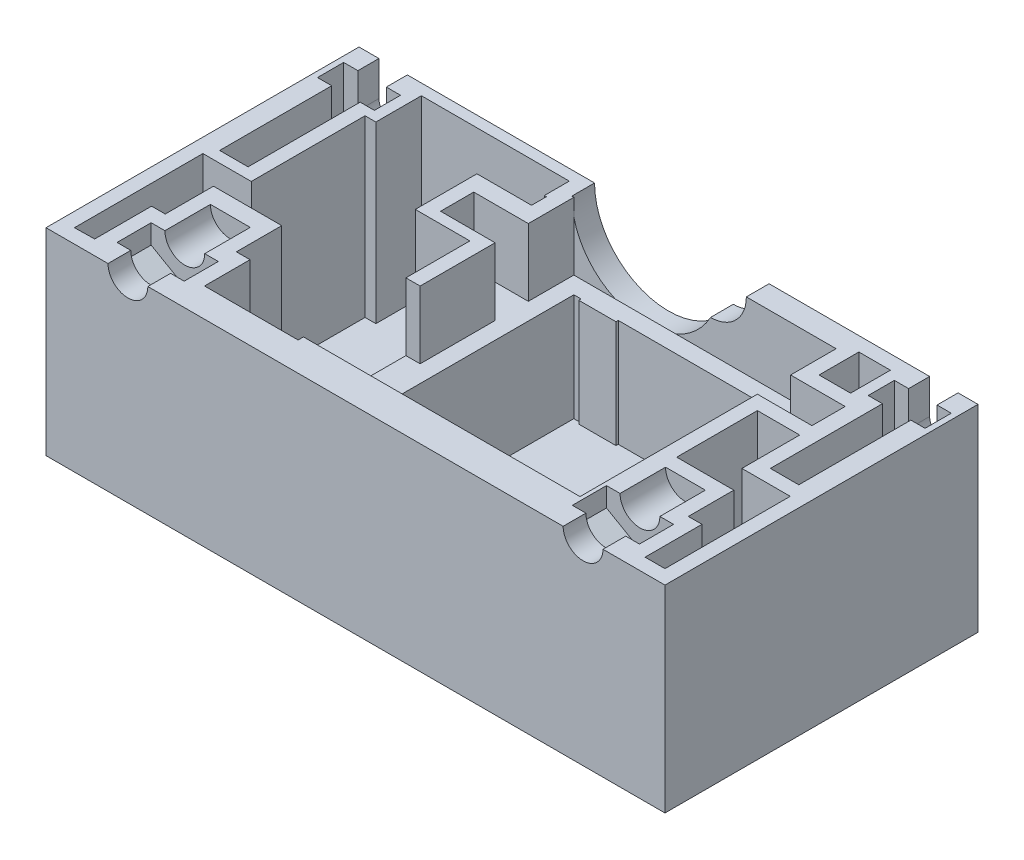
SolidWorks part; units mm, degrees
material "PLA"
ref_plane "Front Plane" through (0, 0, 0) normal (0, 0, 1) x (1, 0, 0)
ref_plane "Top Plane" through (0, 0, 0) normal (0, 1, 0) x (1, 0, 0)
ref_plane "Right Plane" through (0, 0, 0) normal (1, 0, 0) x (0, 0, -1)
sketch "Sketch1" plane through (0, 0, 0) normal (0, 1, 0) x (1, 0, 0)
  line L1 (27.2, -13.755) -> (-27.2, -13.755)
  line L2 (27.2, -13.755) -> (27.2, 13.755)
  line L3 (27.2, 13.755) -> (-27.2, 13.755)
  line L4 (-27.2, -13.755) -> (-27.2, 13.755)
  line L5 (27.2, -13.755) -> (-27.2, 13.755) construction
  line L6 (27.2, 13.755) -> (-27.2, -13.755) construction
  point P0 (0, 0)
  dimension "D1" = 54.4
  dimension "D2" = 27.51
extrude "Boss-Extrude1" add sketch "Sketch1" along normal blind 17.35
sketch "Sketch2" plane through (0, 17.35, 0) normal (0, 1, 0) x (1, 0, 0)
  line L0 (-27.2, -13.755) -> (-25.95, -13.755) construction
  line L1 (-27.2, -13.755) -> (27.2, -13.755) construction
  line L2 (-25.95, -13.755) -> (-25.95, -12.505) construction
  line L19 (-7.75, 12.7853) -> (-20.75, 12.7853)
  line L20 (-25.95, -12.505) -> (-25.95, -1.2147)
  line L21 (-25.95, -1.2147) -> (-21.7, -1.2147)
  line L22 (-21.7, -1.2147) -> (-21.7, 8.7853)
  line L23 (-21.7, 8.7853) -> (-20.75, 8.7853)
  line L26 (-20.75, 12.7853) -> (-20.75, 8.7853)
  line L27 (-7.75, 12.7853) -> (-7.75, 10.5853)
  line L28 (-7.75, 10.5853) -> (-7.57, 10.5853)
  line L29 (-7.57, 10.5853) -> (-7.57, 9.2853)
  line L30 (-7.57, 9.2853) -> (-12.365, 9.2853)
  line L31 (-12.365, 9.2853) -> (-12.365, 3.8653)
  line L32 (-12.365, 3.8653) -> (-7.5693, 3.8653)
  line L33 (-7.5693, 3.8653) -> (-7.5693, -11.2247)
  line L34 (-7.5693, -11.2247) -> (-15.7993, -11.2247)
  line L35 (-15.7993, -11.2247) -> (-15.7993, -7.2247)
  line L36 (-15.7993, -7.2247) -> (-16.9993, -7.2247)
  line L37 (-16.9993, -7.2247) -> (-16.9993, -3.2369)
  line L38 (-16.9993, -3.2369) -> (-22.9993, -3.2369)
  line L39 (-22.9993, -3.2369) -> (-22.9993, -7.4761)
  line L40 (-22.9993, -7.4761) -> (-24.1993, -7.4761)
  line L41 (-24.1993, -7.4761) -> (-24.1993, -12.4761)
  line L42 (-25.95, -12.505) -> (-24.1993, -12.4761)
  dimension "D1" = 1.25
  dimension "D2" = 1.25
  dimension "D3" = 2.2
  dimension "D4" = 0.18
  dimension "D5" = 1.3
  dimension "D6" = 4.795
  dimension "D7" = 5.42
  dimension "D8" = 15.09
  dimension "D9" = 8.23
  dimension "D10" = 4
  dimension "D11" = 1.2
  dimension "D12" = 3.9878
  dimension "D13" = 6
  dimension "D14" = 1.2
  dimension "D15" = 5
  dimension "D17" = 13
  dimension "D19" = 0.95
  dimension "D21" = 4
  dimension "D22" = 10
  dimension "D23" = 11.2903
extrude "Cut-Extrude1" cut sketch "Sketch2" against normal blind 15.35
sketch "Sketch3" plane through (0, 17.35, 0) normal (0, 1, 0) x (1, 0, 0)
  line L0 (-27.2, -13.755) -> (-7.57, -13.755) construction
  line L1 (-27.2, -13.755) -> (27.2, -13.755) construction
  line L2 (-7.57, -13.755) -> (-7.57, -10.755) construction
  line L3 (-7.57, -10.755) -> (-7.57, -1.755)
  line L4 (-7.57, -1.755) -> (-6.32, -1.755)
  line L5 (-6.32, -1.755) -> (-6.32, 11.755)
  line L6 (-6.32, 11.755) -> (16.73, 11.755)
  line L7 (16.73, 11.755) -> (16.73, -10.755)
  line L8 (16.73, -10.755) -> (-7.57, -10.755)
  dimension "D1" = 19.63
  dimension "D2" = 3
  dimension "D3" = 9
  dimension "D4" = 1.25
  dimension "D5" = 13.51
  dimension "D6" = 23.05
extrude "Cut-Extrude2" cut sketch "Sketch3" against normal blind 5.92
sketch "Sketch4" plane through (0, 11.43, 0) normal (0, 1, 0) x (1, 0, 0)
  line L0 (16.73, 11.755) -> (15.23, 10.255) construction
  line L1 (15.23, 10.255) -> (15.23, -9.255)
  line L2 (15.23, -9.255) -> (-4.82, -9.255)
  line L3 (-4.82, -9.255) -> (-4.82, 10.255)
  line L4 (-4.82, 10.255) -> (-4.1839, 10.255)
  line L6 (-4.1839, 10.055) -> (-0.9167, 10.055)
  line L7 (-0.9167, 10.055) -> (-0.9167, 10.255)
  line L8 (15.23, 10.255) -> (-0.9167, 10.255)
  line L9 (-4.1839, 10.255) -> (-4.1839, 10.055)
  dimension "D1" = 1.5
  dimension "D2" = 1.5
  dimension "D3" = 19.51
  dimension "D4" = 19.51
  dimension "D5" = 20.05
  dimension "D6" = 0.2
  dimension "D7" = 0.636
  dimension "D8" = 0.2
extrude "Cut-Extrude3" cut sketch "Sketch4" against normal blind 9.43
sketch "Sketch5" plane through (0, 17.35, 0) normal (0, 1, 0) x (1, 0, 0)
  line L0 (-27.2, 13.755) -> (-11.115, 13.755) construction
  line L1 (27.2, 13.755) -> (-27.2, 13.755) construction
  line L2 (-11.115, 13.755) -> (-11.115, 7.755) construction
  line L3 (-11.115, 7.755) -> (-11.115, 4.835)
  line L4 (-11.115, 4.835) -> (-6.32, 4.835)
  line L5 (-6.32, 11.755) -> (-6.32, -1.755) construction
  line L6 (-6.32, 4.835) -> (-6.32, 7.755)
  line L7 (-6.32, 11.755) -> (-6.32, -1.755) construction
  line L8 (-6.32, 7.755) -> (-11.115, 7.755)
  line L9 (5.205, -9.255) -> (5.205, 21.1558) construction
  line L11 (-4.82, -9.255) -> (15.23, -9.255) construction
  line L12 (21.525, 13.755) -> (21.525, 7.755) construction
  line L13 (16.73, 7.755) -> (21.525, 7.755)
  line L14 (16.73, 4.835) -> (16.73, 7.755)
  line L15 (21.525, 4.835) -> (16.73, 4.835)
  line L16 (21.525, 7.755) -> (21.525, 4.835)
  dimension "D1" = 16.085
  dimension "D2" = 6
  dimension "D3" = 2.92
extrude "Cut-Extrude4" cut sketch "Sketch5" against normal up to surface (5.92 mm away) up to face at (1.3274, 11.43, -5.3275)
sketch "Sketch6" plane through (0, 17.35, 0) normal (0, 1, 0) x (1, 0, 0)
  line L0 (27.2, 13.755) -> (20.75, 13.755) construction
  line L1 (27.2, 13.755) -> (-27.2, 13.755) construction
  line L2 (20.75, 13.755) -> (20.75, 12.505) construction
  line L4 (20.75, 12.505) -> (17.98, 12.505)
  line L5 (20.75, 12.505) -> (20.75, 9.005)
  line L6 (20.75, 9.005) -> (17.98, 9.005)
  line L7 (17.98, 12.505) -> (17.98, 9.005)
  dimension "D1" = 6.45
  dimension "D2" = 1.25
  dimension "D3" = 2.77
  dimension "D4" = 3.5
extrude "Cut-Extrude5" cut sketch "Sketch6" against normal blind 15.35
sketch "Sketch7" plane through (0, 17.35, 0) normal (0, 1, 0) x (1, 0, 0)
  line L0 (27.2, 13.755) -> (27.2, 3.585) construction
  line L1 (27.2, -13.755) -> (27.2, 13.755) construction
  line L2 (27.2, 3.585) -> (21.7, 3.585) construction
  line L3 (21.7, 3.585) -> (17.98, 3.585)
  line L4 (17.98, 3.585) -> (17.98, -3.505)
  line L5 (17.98, -3.505) -> (23, -3.505)
  line L6 (23, -3.505) -> (23, -7.505)
  line L7 (23, -7.505) -> (24.2, -7.505)
  line L8 (24.2, -7.505) -> (24.2, -12.505)
  line L9 (24.2, -12.505) -> (25.95, -12.505)
  line L10 (25.95, -12.505) -> (25.95, -1.495)
  line L11 (25.95, -1.495) -> (21.7, -1.495)
  line L12 (21.7, 3.585) -> (21.7, -1.495)
  dimension "D1" = 5.5
  dimension "D2" = 10.17
  dimension "D3" = 3.72
  dimension "D4" = 7.09
  dimension "D5" = 5.02
  dimension "D6" = 4
  dimension "D7" = 1.2
  dimension "D8" = 5
  dimension "D9" = 1.75
  dimension "D10" = 11.01
  dimension "D11" = 4.25
extrude "Cut-Extrude6" cut sketch "Sketch7" against normal up to surface (15.35 mm away) up to face at (19.365, 2, -10.755)
sketch "Sketch8" plane through (0, 0, 13.755) normal (0, 0, 1) x (1, 0, 0)
  line L0 (-27.2, 17.35) -> (-21.75, 17.35) construction
  line L1 (-27.2, 17.35) -> (27.2, 17.35) construction
  line L2 (-21.75, 17.35) -> (-18.25, 17.35) construction
  line L3 (0, -9.5425) -> (0, 9.5425) construction
  circle A0 centre (-20, 17.35) radius 1.75
  circle A1 centre (20, 17.35) radius 1.75
  dimension "D1" = 5.45
  dimension "D2" = 3.5
extrude "Cut-Extrude7" cut sketch "Sketch8" against normal blind 9
sketch "Sketch9" plane through (0, 0, -13.755) normal (0, 0, -1) x (-1, 0, 0)
  line L0 (-27.2, 17.35) -> (-25.45, 17.35) construction
  line L1 (-27.2, 17.35) -> (27.2, 17.35) construction
  line L2 (-25.45, 17.35) -> (-25.45, 14.3)
  line L3 (0, 9.5425) -> (0, -9.5425) construction
  line L4 (-22.95, 14.3) -> (-22.95, 17.35)
  line L5 (-22.95, 17.35) -> (-25.45, 17.35)
  line L6 (27.2, 17.35) -> (25.45, 17.35) construction
  line L7 (22.95, 17.35) -> (25.45, 17.35)
  line L8 (22.95, 14.3) -> (22.95, 17.35)
  line L9 (25.45, 17.35) -> (25.45, 14.3)
  arc A0 (-25.45, 14.3) -> (-22.95, 14.3) centre (-24.2, 14.3) ccw
  arc A1 (25.45, 14.3) -> (22.95, 14.3) centre (24.2, 14.3) cw
  dimension "D1" = 1.75
  dimension "D2" = 3.05
  dimension "D3" = 2.5
extrude "Cut-Extrude8" cut sketch "Sketch9" against normal blind 14
sketch "Sketch10" plane through (0, 17.35, 0) normal (0, 1, 0) x (1, 0, 0)
  line L0 (-27.2, 13.755) -> (-26.7, 13.755) construction
  line L1 (-25.45, 13.755) -> (-27.2, 13.755) construction
  line L2 (-26.7, 13.755) -> (-26.7, 11.905) construction
  line L3 (-26.7, 11.905) -> (-21.7, 11.905)
  line L4 (-21.7, 11.905) -> (-21.7, 9.605)
  line L5 (-26.7, 11.905) -> (-26.7, 9.605)
  line L6 (-26.7, 9.605) -> (-21.7, 9.605)
  line L7 (0, -9.5425) -> (0, 9.5425) construction
  line L8 (26.7, 11.905) -> (26.7, 9.605)
  line L9 (26.7, 11.905) -> (21.7, 11.905)
  line L10 (21.7, 11.905) -> (21.7, 9.605)
  line L11 (26.7, 9.605) -> (21.7, 9.605)
  dimension "D1" = 0.5
  dimension "D2" = 1.85
  dimension "D3" = 5
  dimension "D4" = 2.3
extrude "Cut-Extrude9" cut sketch "Sketch10" against normal blind 4.3202
ref_plane "Plane1" through (0, 0, -11.755) normal (0, 0, -1) x (-1, 0, 0)
sketch "Sketch11" plane through (0, 0, -11.755) normal (0, 0, -1) x (-1, 0, 0)
  line L0 (-27.2, 17.35) -> (-27.2, 13.0298) construction
  line L1 (-27.2, 17.35) -> (-27.2, 0) construction
  line L2 (-27.2, 13.0298) -> (-26.4, 13.0298) construction
  line L3 (-26.4, 13.0298) -> (-26.4, 11.7597) construction
  line L4 (-26.4, 11.7597) -> (-24.2, 11.7597) construction
  line L5 (-24.2, 11.7597) -> (-24.2, 19.0949) construction
  line L6 (-26.4, 13.0298) -> (-24.2, 11.7597)
  line L7 (-26.4, 13.0298) -> (-22, 13.0298)
  line L8 (-22, 13.0298) -> (-24.2, 11.7597)
  line L9 (0, 9.5425) -> (0, -9.5425) construction
  line L10 (24.2, 11.7597) -> (24.2, 19.0949) construction
  line L11 (26.4, 11.7597) -> (24.2, 11.7597) construction
  line L12 (26.4, 13.0298) -> (26.4, 11.7597) construction
  line L13 (27.2, 13.0298) -> (26.4, 13.0298) construction
  line L14 (27.2, 17.35) -> (27.2, 13.0298) construction
  line L15 (22, 13.0298) -> (24.2, 11.7597)
  line L16 (26.4, 13.0298) -> (22, 13.0298)
  line L17 (26.4, 13.0298) -> (24.2, 11.7597)
  point P11 (-24.2, 13.0298)
  point P20 (24.2, 13.0298)
  dimension "D1" = 0.8
  dimension "D2" = 4.3202
  dimension "D3" = 2.2
  dimension "D4" = 1.2702
extrude "Cut-Extrude10" cut sketch "Sketch11" against normal blind 2
ref_plane "Plane2" through (0, 0, 11.755) normal (0, 0, 1) x (1, 0, 0)
sketch "Sketch13" plane through (0, 0, 11.755) normal (0, 0, 1) x (1, 0, 0)
  line L0 (-27.2, 17.35) -> (-22.9582, 17.35) construction
  line L1 (-27.2, 17.35) -> (-21.75, 17.35) construction
  line L2 (-22.9582, 17.35) -> (-17.0582, 17.35)
  line L3 (-18.25, 17.35) -> (18.25, 17.35) construction
  line L4 (-22.9582, 17.35) -> (-22.9582, 15.6468)
  line L5 (-22.9582, 15.6468) -> (-20.0082, 13.9437)
  line L6 (-17.0582, 17.35) -> (-17.0582, 15.6468)
  line L7 (-17.0582, 15.6468) -> (-20.0082, 13.9437)
  line L8 (0, -9.5425) -> (0, 9.5425) construction
  line L9 (27.2, 17.35) -> (22.9582, 17.35) construction
  line L10 (17.0582, 15.6468) -> (20.0082, 13.9437)
  line L11 (17.0582, 17.35) -> (17.0582, 15.6468)
  line L12 (22.9582, 15.6468) -> (20.0082, 13.9437)
  line L13 (22.9582, 17.35) -> (22.9582, 15.6468)
  line L14 (22.9582, 17.35) -> (17.0582, 17.35)
  dimension "D1" = 5.9
  dimension "D2" = 2.95
  dimension "D3" = 1.7032
  dimension "D4" = 1.7032
extrude "Cut-Extrude11" cut sketch "Sketch13" against normal blind 3
sketch "Sketch14" plane through (0, 0, -13.755) normal (0, 0, -1) x (-1, 0, 0)
  line L0 (-27.2, 17.35) -> (-8.84, 17.35) construction
  line L1 (-22.95, 17.35) -> (22.95, 17.35) construction
  line L2 (-8.84, 17.35) -> (6.5, 17.35)
  line L3 (-8.84, 17.35) -> (-8.84, 14.4012) construction
  line L4 (-8.84, 14.4012) -> (-6.7692, 14.4012) construction
  line L5 (-6.7692, 14.4012) -> (-6.7692, 14.215) construction
  line L6 (-6.7692, 14.215) -> (-5.694, 14.215) construction
  line L7 (-8.84, 17.35) -> (-5.7051, 17.35) construction
  line L8 (-5.694, 14.215) -> (-5.694, 10.8519) construction
  line L9 (-5.694, 10.8519) -> (-0.159, 10.8519) construction
  line L10 (6.5, 17.35) -> (0, 17.35) construction
  arc A1 (-8.84, 17.35) -> (-2.5702, 17.35) centre (-5.7051, 17.35) ccw
  arc A3 (-6.5, 17.35) -> (6.5, 17.35) centre (0, 17.35) ccw
  dimension "D1" = 18.36
  dimension "D2" = 15.34
  dimension "D3" = 2.0708
  dimension "D4" = 2.9488
  dimension "D5" = 1.0752
  dimension "D6" = 0.1861
  dimension "D7" = 3.1349
  dimension "D8" = 5.535
  dimension "D9" = 3.3631
extrude "Cut-Extrude12" cut sketch "Sketch14" against normal up to surface (2 mm away) contours A3 L1 A1 | L2 A3 A1 | A1 A3 L1 up to face at (5.205, 14.39, -11.755)
